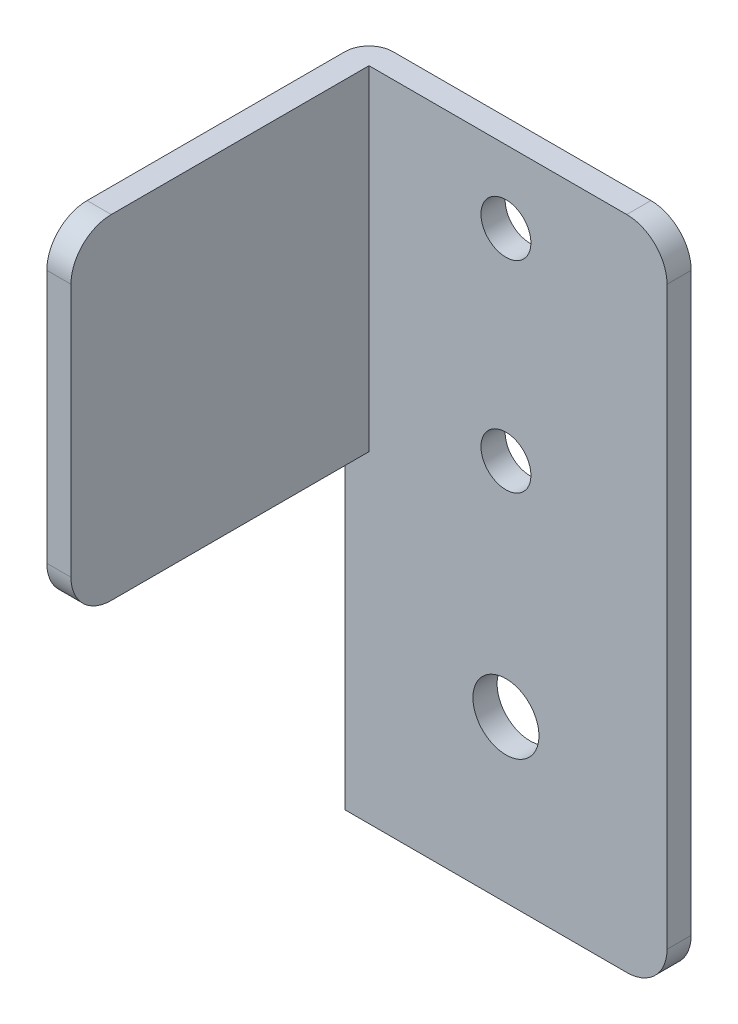
SolidWorks part; units mm, degrees
ref_plane "Front" through (0, 0, 0) normal (0, 0, 1) x (1, 0, 0)
ref_plane "Top" through (0, 0, 0) normal (0, 1, 0) x (1, 0, 0)
ref_plane "Right" through (0, 0, 0) normal (1, 0, 0) x (0, 0, -1)
sketch "Sketch1" plane through (0, 0, 0) normal (0, 1, 0) x (1, 0, 0)
  line L0 (0, -3) -> (0, -40)
  line L1 (3, 0) -> (40, 0)
  arc A0 (0, -3) -> (3, 0) centre (3, -3) cw
  point P6 (0, 0)
  dimension "D3" = 3
  dimension "D1" = 40
  dimension "D2" = 40
extrude "Extrude-Thin1" add sketch "Sketch1" along normal blind 81.5 thin
sketch "Sketch2" plane through (3, 0, 0) normal (1, 0, 0) x (0, 0, -1)
  line L0 (-40, 81.5) -> (-40, 0) construction
  line L1 (-3, 0) -> (-40, 0)
  line L2 (-3, 0) -> (-3, 40)
  line L3 (-3, 40) -> (-40, 40)
  line L4 (-40, 0) -> (-40, 40)
  dimension "D1" = 40
extrude "Cut-Extrude1" cut sketch "Sketch2" against normal blind 10
sketch "Sketch3" plane through (0, 0, 0) normal (0, 0, -1) x (-1, 0, 0)
  line L0 (-3, 0) -> (-40, 0) construction
  line L1 (-40, 81.5) -> (-40, 0) construction
  circle A0 centre (-20, 20) radius 4.1
  dimension "D1" = 8.2
  dimension "D2" = 20
  dimension "D3" = 20
extrude "Cut-Extrude2" cut sketch "Sketch3" against normal blind 10
sketch "Sketch4" plane through (0, 0, 0) normal (0, 0, -1) x (-1, 0, 0)
  circle A0 centre (-20, 47.5) radius 3.1
  circle A1 centre (-20, 72.5) radius 3.1
  dimension "D1" = 6.2
extrude "Cut-Extrude3" cut sketch "Sketch4" against normal blind 10
fillet "Fillet1" radius 5 4 edges at (1.5, 81.5, 40) (1.5, 40, 40) (40, 0, 1.5) (40, 81.5, 1.5)
